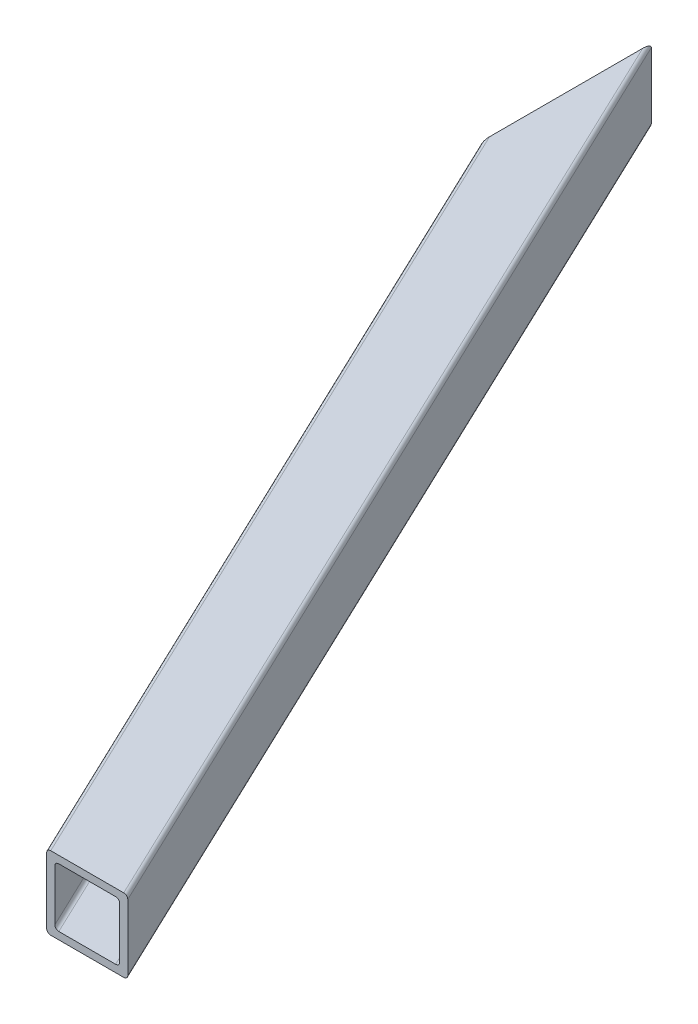
SolidWorks part; units mm, degrees
ref_plane "Plan de face" through (0, 0, 0) normal (0, 0, 1) x (1, 0, 0)
ref_plane "Plan de dessus" through (0, 0, 0) normal (0, 1, 0) x (1, 0, 0)
ref_plane "Plan de droite" through (0, 0, 0) normal (1, 0, 0) x (0, 0, -1)
sketch "Esquisse1" plane through (0, 0, 0) normal (0, 1, 0) x (1, 0, 0)
  line L0 (0, 0) -> (0, 452.9624) construction
  line L1 (0, 452.9624) -> (215.6964, 0)
  line L2 (215.6964, 0) -> (0, 0) construction
  line L3 (215.6964, 0) -> (260, 0)
  line L4 (260, 0) -> (0, 546)
  line L5 (0, 452.9624) -> (0, 546)
  dimension "D1" = 40
  dimension "D2" = 260
  dimension "D3" = 546
extrude "Boss.-Extru.1" add sketch "Esquisse1" along normal blind 40
shell "Coque1" thickness 4
ref_plane "Plan1" through (39.8699, 0, 83.7269) normal (-0.4299, 0, -0.9029) x (0, -1, 0)
sketch "Esquisse2" plane through (39.8699, 0, 83.7269) normal (-0.4299, 0, -0.9029) x (0, -1, 0)
  line L0 (-40, -234.7437) -> (-40, -194.7437) construction
  line L1 (-36, -198.7437) -> (-4, -198.7437)
  line L2 (-36, -198.7437) -> (-36, -230.7437)
  line L3 (-36, -230.7437) -> (-4, -230.7437)
  line L4 (-4, -198.7437) -> (-4, -230.7437)
  line L5 (-40, -194.7437) -> (0, -194.7437) construction
  line L6 (-40, -234.7437) -> (0, -234.7437) construction
  line L7 (0, -234.7437) -> (0, -194.7437) construction
  dimension "D1" = 4
  dimension "D2" = 4
  dimension "D3" = 4
  dimension "D4" = 4
extrude "Enlèv. mat.-Extru.1" cut sketch "Esquisse2" against normal through all both and the other way through all
fillet "Congé1" radius 2 8 edges at (107.8482, 40, -226.4812) (127.7848, 36, -268.3481) (110.0634, 36, -231.1331) (110.0634, 4, -231.1331) (127.7848, 4, -268.3481) (130, 40, -273) (107.8482, 0, -226.4812) (130, 0, -273)
